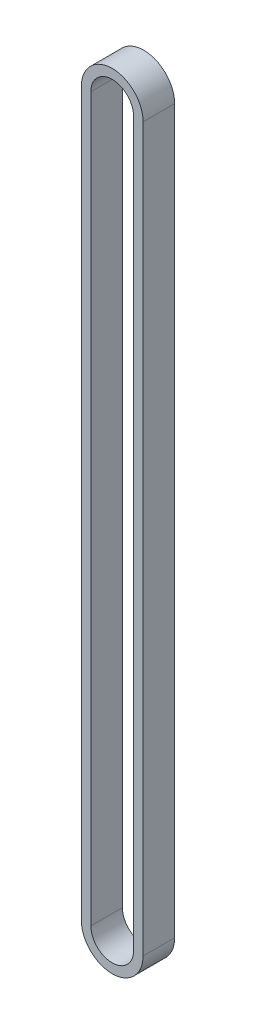
SolidWorks part; units mm, degrees
material "天然橡胶"
ref_plane "前视基准面" through (0, 0, 0) normal (0, 0, 1) x (1, 0, 0)
ref_plane "上视基准面" through (0, 0, 0) normal (0, 1, 0) x (1, 0, 0)
ref_plane "右视基准面" through (0, 0, 0) normal (1, 0, 0) x (0, 0, -1)
other "Configuration Table"
sketch "草图1" plane through (0, 0, 0) normal (0, 0, 1) x (1, 0, 0)
  line L0 (0, -114.5) -> (0, 114.5) construction
  line L1 (-6.78, -114.5) -> (-6.78, 114.5)
  line L2 (6.78, -114.5) -> (6.78, 114.5)
  line L3 (-9.78, -114.5) -> (-9.78, 114.5)
  line L4 (9.78, -114.5) -> (9.78, 114.5)
  arc A0 (-6.78, -114.5) -> (6.78, -114.5) centre (0, -114.5) ccw
  arc A1 (6.78, 114.5) -> (-6.78, 114.5) centre (0, 114.5) ccw
  arc A2 (9.78, 114.5) -> (-9.78, 114.5) centre (0, 114.5) ccw
  arc A3 (-9.78, -114.5) -> (9.78, -114.5) centre (0, -114.5) ccw
  point P2 (0, 0)
  dimension "D2" = 6.78
  dimension "D1" = 229
  dimension "D3" = 3
extrude "凸台-拉伸1" add sketch "草图1" along normal blind 10
